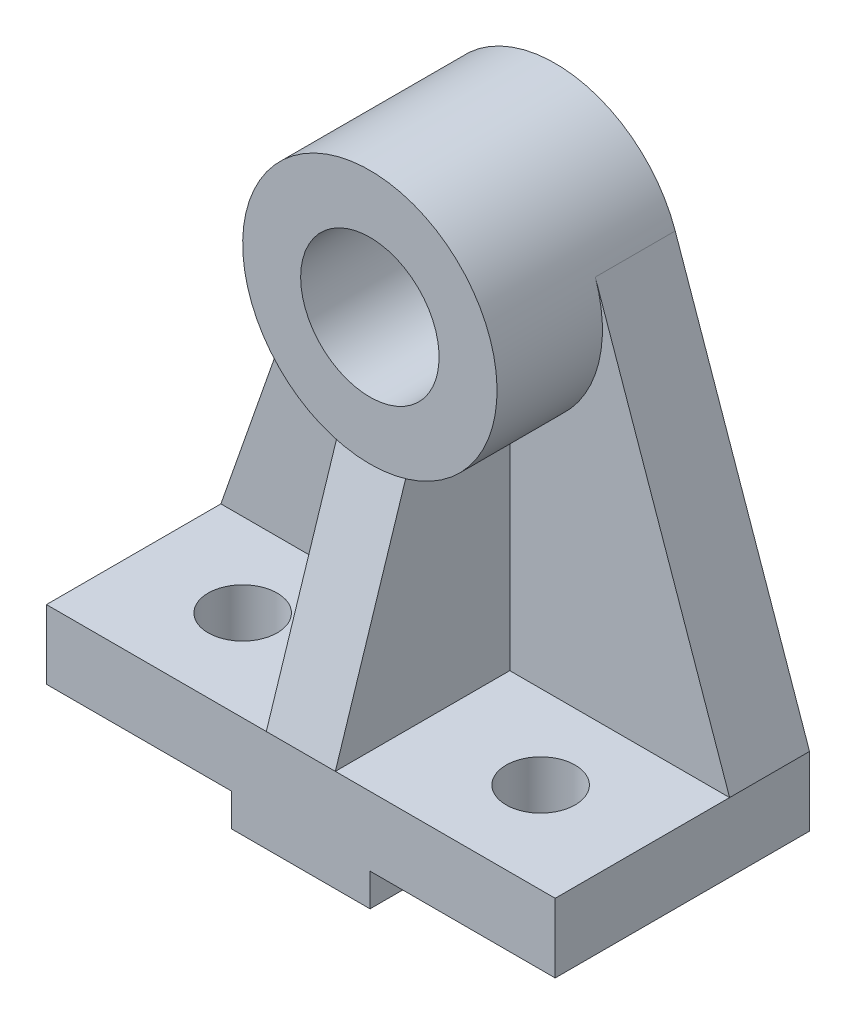
SolidWorks part; units mm, degrees
ref_plane "Front Plane" through (0, 0, 0) normal (0, 0, 1) x (1, 0, 0)
ref_plane "Top Plane" through (0, 0, 0) normal (0, 1, 0) x (1, 0, 0)
ref_plane "Right Plane" through (0, 0, 0) normal (1, 0, 0) x (0, 0, -1)
sketch "Sketch1" plane through (0, 0, 0) normal (0, 1, 0) x (1, 0, 0)
  line L1 (-70, -35) -> (70, -35)
  line L2 (-70, -35) -> (-70, 35)
  line L3 (-70, 35) -> (70, 35)
  line L4 (70, -35) -> (70, 35)
  line L5 (-70, -35) -> (70, 35) construction
  line L6 (-70, 35) -> (70, -35) construction
  point P0 (0, 0)
  dimension "D1" = 70
  dimension "D2" = 140
extrude "Boss-Extrude1" add sketch "Sketch1" along normal blind 19
sketch "Sketch2" plane through (0, 0, 35) normal (0, 0, 1) x (1, 0, 0)
  line L0 (-70, 0) -> (70, 0) construction
  line L1 (-19.05, -9) -> (19.05, -9)
  line L2 (-19.05, -9) -> (-19.05, 0)
  line L3 (-19.05, 0) -> (19.05, 0)
  line L4 (19.05, -9) -> (19.05, 0)
  line L5 (-19.05, -9) -> (19.05, 0) construction
  line L6 (-19.05, 0) -> (19.05, -9) construction
  point P0 (0, -4.5)
  dimension "D1" = 9
  dimension "D2" = 38.1
extrude "Boss-Extrude2" add sketch "Sketch2" against normal up to surface (70 mm away) up to face at (0, 9.5, -35)
sketch "Sketch3" plane through (0, 19, 0) normal (0, 1, 0) x (1, 0, 0)
  line L0 (0, -6.9665) -> (0, 10.4124) construction
  line L2 (70, 35) -> (-70, 35) construction
  circle A0 centre (41, -10) radius 9.5
  circle A1 centre (-41, -10) radius 9.5
  dimension "D2" = 19
  dimension "D1" = 82
  dimension "D3" = 45
extrude "Cut-Extrude1" cut sketch "Sketch3" against normal through all
sketch "Sketch4" plane through (0, 0, -35) normal (0, 0, -1) x (-1, 0, 0)
  line L0 (-70, 19) -> (70, 19) construction
  circle A0 centre (0, 113) radius 35
  circle A1 centre (0, 113) radius 19.05
  dimension "D1" = 70
  dimension "D2" = 38.1
  dimension "D3" = 94
extrude "Boss-Extrude3" add sketch "Sketch4" against normal blind 51 separate body
sketch "Sketch7" plane through (0, 0, -35) normal (0, 0, -1) x (-1, 0, 0)
  line L0 (-70, 19) -> (-33.0333, 124.5673)
  line L1 (33.0333, 124.5673) -> (70, 19)
  line L2 (70, 19) -> (-70, 19)
  circle A0 centre (0, 113) radius 35 construction
  arc A1 (-33.0333, 124.5673) -> (33.0333, 124.5673) centre (0, 113) ccw
extrude "Boss-Extrude4" add sketch "Sketch7" against normal blind 22
sketch "Sketch10" plane through (0, 0, 0) normal (1, 0, 0) x (0, 0, -1)
  line L0 (-35, 19) -> (-16, 78)
rib "Rib5" sketch "Sketch10" sketch "Sketch10" thickness 19 extrusion direction parallel to sketch draft on no parameters "D1"=19
